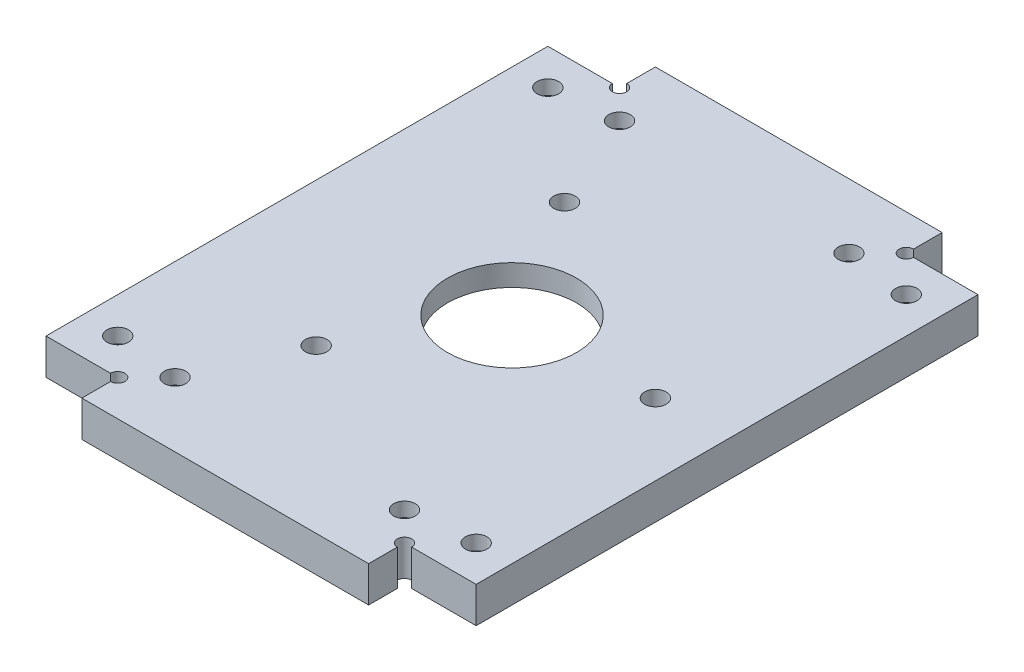
SolidWorks part; units mm, degrees
ref_plane "前视基准面" through (0, 0, 0) normal (0, 0, 1) x (1, 0, 0)
ref_plane "上视基准面" through (0, 0, 0) normal (0, 1, 0) x (1, 0, 0)
ref_plane "右视基准面" through (0, 0, 0) normal (1, 0, 0) x (0, 0, -1)
other "Configuration Table"
sketch "草图1" plane through (0, 0, 0) normal (0, 1, 0) x (1, 0, 0)
  line L1 (-30, 40) -> (30, 40)
  line L2 (-30, 40) -> (-30, -40)
  line L3 (-30, -40) -> (30, -40)
  line L4 (30, 40) -> (30, -40)
  line L5 (-30, 40) -> (30, -40) construction
  line L6 (-30, -40) -> (30, 40) construction
  point P0 (0, 0)
  dimension "D1" = 60
  dimension "D2" = 80
extrude "凸台-拉伸1" add sketch "草图1" along normal blind 5
sketch "草图2" plane through (0, 5, 0) normal (0, 1, 0) x (1, 0, 0)
  circle A0 centre (0, 0) radius 20 construction
  circle A1 centre (20, 0) radius 1.5
  circle A2 centre (-10, -17.3205) radius 1.5
  circle A3 centre (-10, 17.3205) radius 1.5
  circle A4 centre (0, 0) radius 9
  point P12 (0, 0)
  dimension "D1" = 40
  dimension "D3" = 3
  dimension "D4" = 18
  dimension "D2" = 3
extrude "切除-拉伸1" cut sketch "草图2" against normal through all
sketch "草图3" plane through (0, 5, 0) normal (0, 1, 0) x (1, 0, 0)
  line L0 (30, -40) -> (30, 40) construction
  line L1 (-25, -30) -> (25, -30) construction
  line L2 (-25, -30) -> (-25, 30) construction
  line L3 (-25, 30) -> (25, 30) construction
  line L4 (25, -30) -> (25, 30) construction
  line L5 (-25, -30) -> (25, 30) construction
  line L6 (-25, 30) -> (25, -30) construction
  line L7 (-30, -40) -> (30, -40) construction
  line L8 (0, 0) -> (0, 30) construction
  line L9 (0, 0) -> (25, 0) construction
  line L10 (-16, -31) -> (16, -31) construction
  line L11 (0, 0) -> (0, -31) construction
  circle A1 centre (-25, 30) radius 1.5
  circle A2 centre (25, 30) radius 1.5
  circle A3 centre (-25, -30) radius 1.5
  circle A4 centre (25, -30) radius 1.5
  circle A9 centre (-16, -31) radius 1.5
  circle A10 centre (16, -31) radius 1.5
  circle A11 centre (16, 31) radius 1.5
  circle A12 centre (-16, 31) radius 1.5
  point P0 (0, 0)
  dimension "D1" = 3
  dimension "D5" = 3
  dimension "D2" = 5
  dimension "D3" = 10
  dimension "D4" = 32
  dimension "D6" = 9
extrude "切除-拉伸2" cut sketch "草图3" against normal through all
sketch "草图4" plane through (0, 0, 0) normal (0, -1, 0) x (1, 0, 0)
  circle A0 centre (-25, 30) radius 3
  circle A1 centre (25, 30) radius 3
  circle A2 centre (25, -30) radius 3
  circle A3 centre (-25, -30) radius 3
  circle A4 centre (-16, 31) radius 3
  circle A5 centre (16, 31) radius 3
  circle A6 centre (-16, -31) radius 3
  circle A7 centre (16, -31) radius 3
  dimension "D1" = 6
extrude "切除-拉伸3" cut sketch "草图4" against normal blind 3
sketch "草图5" plane through (0, 5, 0) normal (0, 1, 0) x (1, 0, 0)
  line L0 (0, 0) -> (0, -40) construction
  line L1 (-30, -40) -> (-20, -40)
  line L2 (-30, -40) -> (-30, -35)
  line L3 (-30, -35) -> (-20, -35)
  line L4 (-20, -40) -> (-20, -35)
  line L5 (-30, -40) -> (30, -40) construction
  line L6 (0, 0) -> (-30, 0) construction
  line L7 (-30, 40) -> (-30, -40) construction
  line L8 (20, -40) -> (20, -35)
  line L9 (30, -35) -> (20, -35)
  line L10 (30, -40) -> (30, -35)
  line L11 (30, -40) -> (20, -40)
  line L12 (30, 40) -> (20, 40)
  line L13 (30, 40) -> (30, 35)
  line L14 (30, 35) -> (20, 35)
  line L15 (20, 40) -> (20, 35)
  line L16 (-20, 40) -> (-20, 35)
  line L17 (-30, 35) -> (-20, 35)
  line L18 (-30, 40) -> (-30, 35)
  line L19 (-30, 40) -> (-20, 40)
  circle A0 centre (-20, -35) radius 1
  circle A1 centre (20, -35) radius 1
  circle A2 centre (20, 35) radius 1
  circle A3 centre (-20, 35) radius 1
  circle M7 centre (25, 30) radius 1.5
  circle M8 centre (-25, -30) radius 1.5
  circle M9 centre (25, -30) radius 1.5
  circle M10 centre (-25, 30) radius 1.5
  circle M11 centre (20, 0) radius 1.5
  circle M12 centre (-10, -17.3205) radius 1.5
  circle M13 centre (-10, 17.3205) radius 1.5
  line M14 (30, -40) -> (30, 40)
  line M15 (30, 40) -> (-30, 40)
  line M16 (-30, 40) -> (-30, -40)
  line M17 (-30, -40) -> (30, -40)
  dimension "D3" = 2
  dimension "D1" = 5
  dimension "D2" = 10
extrude "切除-拉伸4" cut sketch "草图5" against normal through all flip side to cut contours L16 A3 L17 L3 A0 L4 L8 A1 L9 L14 A2 L15 M16 M17 M14 M15 M8 M10 M12 M13 M11 M9 M7
sketch "草图6" plane through (0, 0, 0) normal (0, -1, 0) x (1, 0, 0)
  circle A0 centre (0, 0) radius 12
  dimension "D1" = 24
extrude "切除-拉伸5" cut sketch "草图6" against normal blind 2
